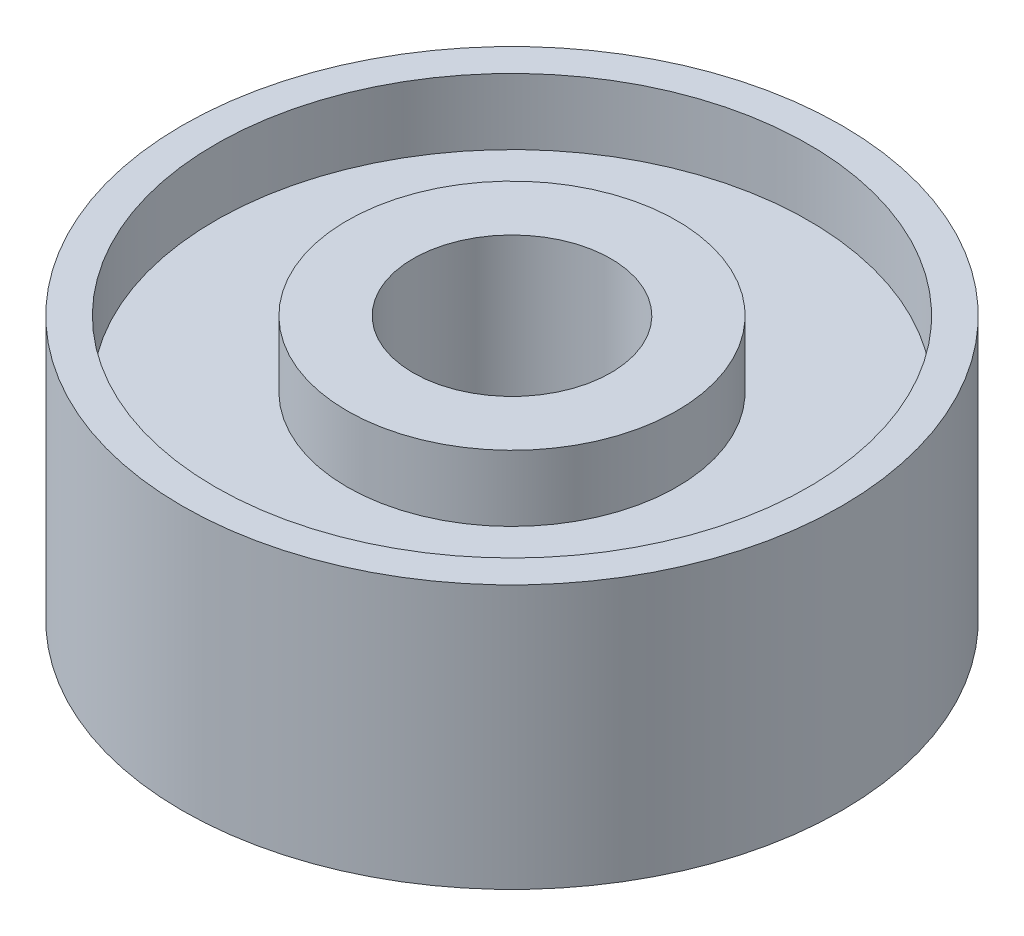
SolidWorks part; units mm, degrees
ref_plane "Спереди" through (0, 0, 0) normal (0, 0, 1) x (1, 0, 0)
ref_plane "Сверху" through (0, 0, 0) normal (0, 1, 0) x (1, 0, 0)
ref_plane "Справа" through (0, 0, 0) normal (1, 0, 0) x (0, 0, -1)
sketch "Эскиз1" plane through (0, 0, 0) normal (0, 1, 0) x (1, 0, 0)
  circle A0 centre (0, 0) radius 1.5
  circle A1 centre (0, 0) radius 5
extrude "Бобышка-Вытянуть1" add sketch "Эскиз1" along normal blind 4
sketch "Эскиз2" plane through (0, 4, 0) normal (0, 1, 0) x (1, 0, 0)
  circle A0 centre (0, 0) radius 2.5
  circle A1 centre (0, 0) radius 4.5
extrude "Вырез-Вытянуть1" cut sketch "Эскиз2" against normal blind 1
sketch "Эскиз3" plane through (0, 0, 0) normal (0, -1, 0) x (1, 0, 0)
  circle A0 centre (0, 0) radius 2.5
  circle A1 centre (0, 0) radius 4.5
extrude "Вырез-Вытянуть2" cut sketch "Эскиз3" against normal blind 1
